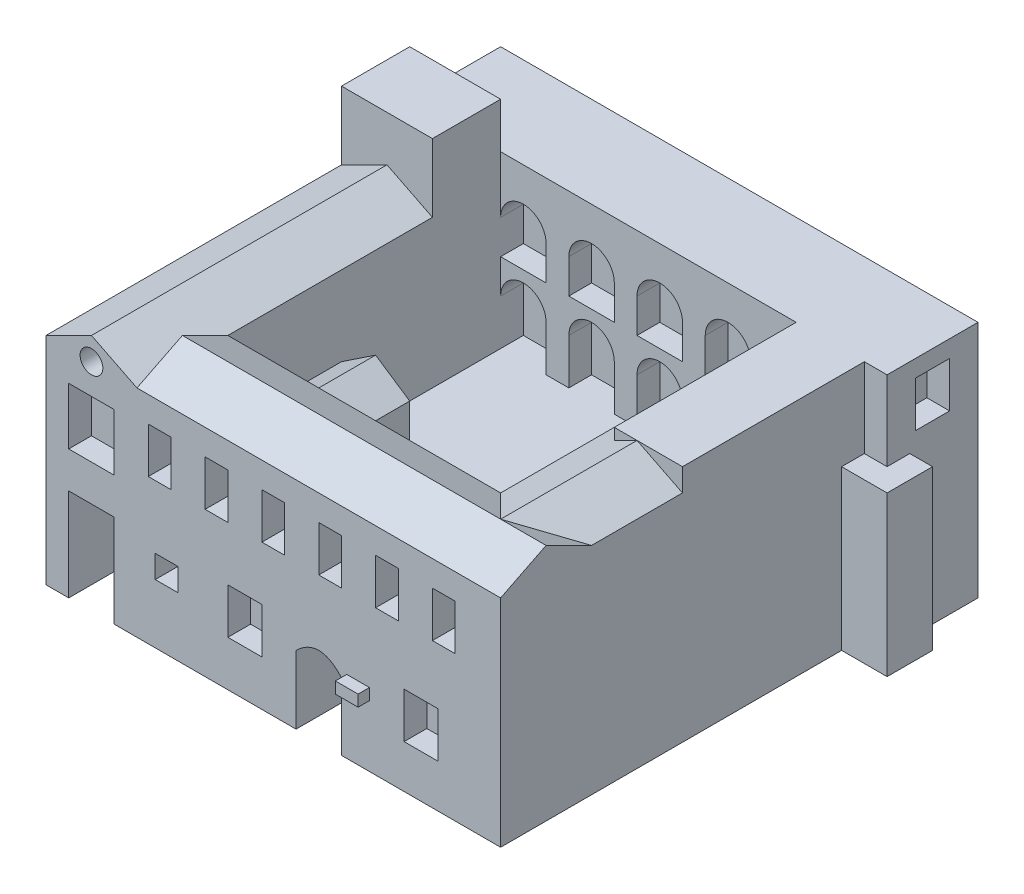
SolidWorks part; units mm, degrees
ref_plane "Alzado" through (0, 0, 0) normal (0, 0, 1) x (1, 0, 0)
ref_plane "Planta" through (0, 0, 0) normal (0, 1, 0) x (1, 0, 0)
ref_plane "Vista lateral" through (0, 0, 0) normal (1, 0, 0) x (0, 0, -1)
sketch "Croquis1" plane through (0, 0, 0) normal (0, 1, 0) x (1, 0, 0)
  line L1 (-10, -10) -> (10, -10)
  line L2 (-10, -10) -> (-10, 10)
  line L3 (-10, 10) -> (10, 10)
  line L4 (10, -10) -> (10, 10)
  line L5 (-10, -10) -> (10, 10) construction
  line L6 (-10, 10) -> (10, -10) construction
  point P0 (0, 0)
  dimension "D1" = 20
  dimension "D2" = 20
extrude "Saliente-Extruir1" add sketch "Croquis1" along normal blind 2
sketch "Croquis2" plane through (0, 2, 0) normal (0, 1, 0) x (1, 0, 0)
  line L0 (-10, 10) -> (-10, -10) construction
  line L1 (-6, -6) -> (6, -6)
  line L2 (-6, -6) -> (-6, 6)
  line L3 (-6, 6) -> (6, 6)
  line L4 (6, -6) -> (6, 6)
  line L5 (-6, -6) -> (6, 6) construction
  line L6 (-6, 6) -> (6, -6) construction
  line L7 (10, 10) -> (-10, 10) construction
  line L12 (10, -10) -> (10, 10)
  line L13 (10, 10) -> (-10, 10)
  line L14 (-10, 10) -> (-10, -10)
  line L15 (-10, -10) -> (10, -10)
  line L16 (10, -10) -> (10, 10)
  line L17 (10, 10) -> (-10, 10)
  line L18 (-10, 10) -> (-10, -10)
  line L19 (-10, -10) -> (10, -10)
  point P0 (0, 0)
  dimension "D1" = 4
  dimension "D2" = 4
  dimension "D3" = 0
extrude "Saliente-Extruir2" add sketch "Croquis2" along normal blind 6.5
sketch "Croquis3" plane through (0, 8.5, 0) normal (0, 1, 0) x (1, 0, 0)
  line L0 (-6, 6) -> (-10, 6) construction
  line L1 (-10, 10) -> (-10, -10) construction
  line L2 (-10, 6) -> (-10, 3) construction
  line L3 (-10, 3) -> (-6, 3) construction
  line L4 (-6, 6) -> (-6, -6) construction
  line L5 (-6, 3) -> (-6, 6) construction
  line L6 (-10, 6) -> (-6, 6)
  line L7 (-6, 6) -> (-6, 3)
  line L8 (-6, 3) -> (-10, 3)
  line L9 (-10, 3) -> (-10, 6)
  dimension "D1" = 3
extrude "Saliente-Extruir3" add sketch "Croquis3" along normal blind 3
sketch "Croquis4" plane through (0, 0, 10) normal (0, 0, 1) x (1, 0, 0)
  line L0 (-10, 8.5) -> (-6, 8.5) construction
  line L1 (-10, 8.5) -> (-8, 9.5)
  line L2 (-8, 9.5) -> (-6, 8.5)
  line L3 (-10, 8.5) -> (-6, 8.5)
  line L4 (-8, 8.5) -> (-8, 10.5037) construction
  dimension "D1" = 1
extrude "Saliente-Extruir4" add sketch "Croquis4" against normal up to surface (13 mm away) up to face at (-8, 10, -3)
sketch "Croquis5" plane through (10, 0, 0) normal (1, 0, 0) x (0, 0, -1)
  line L0 (-10, 8.5) -> (-8, 9.5)
  line L1 (-8, 9.5) -> (-6, 8.5)
  line L2 (-6, 8.5) -> (-10, 8.5)
  line L3 (-8, 8.5) -> (-8, 9.5623) construction
  line L4 (3, 9.5) -> (-10, 9.5) construction
extrude "Saliente-Extruir5" add sketch "Croquis5" against normal blind 16
sketch "Croquis6" plane through (0, 0, -10) normal (0, 0, -1) x (-1, 0, 0)
  line L0 (-10, 8.5) -> (-6, 8.5)
  line L1 (-6, 8.5) -> (-8, 9.5)
  line L2 (6, 9.5) -> (-10, 9.5) construction
  line L3 (-8, 9.5) -> (-10, 8.5)
  line L4 (-8, 8.5) -> (-8, 10.4403) construction
extrude "Saliente-Extruir6" add sketch "Croquis6" against normal up to surface (16 mm away)
sketch "Croquis7" plane through (0, 8.5, 0) normal (0, 1, 0) x (1, 0, 0)
  line L0 (6, 10) -> (10, 10)
  line L1 (10, 10) -> (10, -2)
  line L2 (10, -6) -> (10, 10) construction
  line L3 (10, -2) -> (7, -2)
  line L4 (7, -2) -> (7, 6)
  line L5 (6, 6) -> (6, 10)
  line L6 (6, 10) -> (-10, 10)
  line L7 (-10, 10) -> (-10, 6)
  line L8 (-10, 6) -> (-6, 6)
  line L9 (-6, 6) -> (6, 6)
  line L11 (6, 10) -> (-10, 10)
  line L12 (-10, 10) -> (-10, 6)
  line L13 (-10, 6) -> (-6, 6)
  line L14 (-6, 6) -> (6, 6)
  line L15 (7, 6) -> (6, 6)
  dimension "D2" = 3
  dimension "D3" = 12
  dimension "D1" = 0
extrude "Saliente-Extruir7" add sketch "Croquis7" along normal blind 1
sketch "Croquis8" plane through (0, 0, 0) normal (0, 1, 0) x (1, 0, 0)
  line L0 (10, 10) -> (11, 10)
  line L1 (11, 10) -> (11, 6)
  line L2 (11, 6) -> (10, 6)
  line L3 (10, -2) -> (10, 10) construction
  line L4 (10, 10) -> (10, 6)
  dimension "D1" = 1
  dimension "D2" = 4
extrude "Saliente-Extruir8" add sketch "Croquis8" along normal up to surface (9.5 mm away) up to face at (2, 9.5, -4)
sketch "Croquis9" plane through (0, 0, 0) normal (0, 1, 0) x (1, 0, 0)
  line L0 (10, -2) -> (10, 6) construction
  line L1 (12, 7) -> (10, 7)
  line L2 (12, 7) -> (12, 5)
  line L3 (12, 5) -> (10, 5)
  line L4 (10, 7) -> (10, 5)
  line L5 (12, 7) -> (10, 5) construction
  line L6 (12, 5) -> (10, 7) construction
  point P0 (11, 6)
  dimension "D1" = 2
extrude "Saliente-Extruir9" add sketch "Croquis9" along normal blind 6
sketch "Croquis10" plane through (0, 2, 0) normal (0, 1, 0) x (1, 0, 0)
  line L0 (-6, -6) -> (-6, -5)
  line L1 (-6, 3) -> (-6, -6) construction
  line L2 (-6, -5) -> (6, -5)
  line L3 (6, -6) -> (6, 6) construction
  line L4 (6, -5) -> (6, -6)
  line L5 (-6, -6) -> (6, -6) construction
  line L6 (6, -6) -> (-6, -6)
  dimension "D1" = 1
extrude "Saliente-Extruir10" add sketch "Croquis10" along normal blind 4
sketch "Croquis12" plane through (0, 0, 5) normal (0, 0, -1) x (-1, 0, 0)
  line L2 (3, 5) -> (3, 2)
  line L3 (-6, 2) -> (6, 2) construction
  line L4 (3, 2) -> (6, 2)
  line L5 (6, 2) -> (6, 5)
  line L6 (4.5, 6) -> (4.5, 5) construction
  line L7 (4.5, 5) -> (6, 5) construction
  line L8 (6, 5) -> (3, 5) construction
  line L9 (3, 5) -> (4.5, 6)
  line L10 (4.5, 6) -> (6, 5)
  dimension "D2" = 1
extrude "Saliente-Extruir11" add sketch "Croquis12" along normal blind 4
sketch "Croquis13" plane through (0, 0, 10) normal (0, 0, 1) x (1, 0, 0)
  line L0 (-10, 0) -> (-6, 0) construction
  line L1 (10, 0) -> (10, 8.5) construction
  line L2 (-6, 8.5) -> (10, 8.5) construction
  line L3 (-6, 8.5) -> (10, 8.5) construction
  line L4 (-10, 8.5) -> (-10, 0) construction
  line L5 (-10, 8.5) -> (-6, 8.5) construction
  line L6 (-6, 2.125) -> (1, 2) construction
  line L7 (-9, 0) -> (-7, 0)
  line L9 (-9, 0) -> (-9, 3.0778)
  line L10 (-9, 3.0778) -> (-7, 3.0778)
  line L11 (-7, 0) -> (-7, 3.0778)
  line L12 (-8, 0) -> (-7, 3.0778) construction
  line L13 (-9, 3.0778) -> (-8, 0) construction
  line L14 (-6, 4.25) -> (-10, 4.25) construction
  line L15 (-10, 4.25) -> (-10, 8.5) construction
  line L16 (-6, 4.25) -> (-6, 0) construction
  line L17 (-9, 4.6763) -> (-7, 4.6763)
  line L18 (-9, 4.6763) -> (-9, 7.1763)
  line L19 (-9, 7.1763) -> (-7, 7.1763)
  line L20 (-7, 4.6763) -> (-7, 7.1763)
  line L21 (-9, 4.6763) -> (-7, 7.1763) construction
  line L22 (-9, 7.1763) -> (-7, 4.6763) construction
  line L23 (-6, 0) -> (10, 0) construction
  line L24 (1, 0) -> (1, 2)
  line L26 (3, 1.9643) -> (3, 0)
  line L27 (2, 2) -> (2, 2.5) construction
  line L28 (2.2667, 2.5) -> (1.7333, 2.5) construction
  line L29 (-6, 4.25) -> (-6, 8.5) construction
  line L30 (-6, 6.375) -> (10, 6.375) construction
  line L31 (1, 0) -> (3, 0)
  line L32 (-5.5, 7.375) -> (-4.5, 7.375)
  line L33 (-5.5, 7.375) -> (-5.5, 5.375)
  line L34 (-5.5, 5.375) -> (-4.5, 5.375)
  line L35 (-4.5, 7.375) -> (-4.5, 5.375)
  line L36 (-5.5, 7.375) -> (-4.5, 5.375) construction
  line L37 (-5.5, 5.375) -> (-4.5, 7.375) construction
  line L38 (-3, 5.375) -> (-2, 5.375)
  line L39 (-3, 5.375) -> (-3, 7.375)
  line L40 (-3, 7.375) -> (-2, 7.375)
  line L41 (-2, 5.375) -> (-2, 7.375)
  line L42 (-3, 5.375) -> (-2, 7.375) construction
  line L43 (-3, 7.375) -> (-2, 5.375) construction
  line L44 (-0.5, 5.375) -> (0.5, 5.375)
  line L45 (-0.5, 5.375) -> (-0.5, 7.375)
  line L46 (-0.5, 7.375) -> (0.5, 7.375)
  line L47 (0.5, 5.375) -> (0.5, 7.375)
  line L48 (-0.5, 5.375) -> (0.5, 7.375) construction
  line L49 (-0.5, 7.375) -> (0.5, 5.375) construction
  line L50 (2, 5.375) -> (3, 5.375)
  line L51 (2, 5.375) -> (2, 7.375)
  line L52 (2, 7.375) -> (3, 7.375)
  line L53 (3, 5.375) -> (3, 7.375)
  line L54 (2, 5.375) -> (3, 7.375) construction
  line L55 (2, 7.375) -> (3, 5.375) construction
  line L56 (4.5, 5.375) -> (5.5, 5.375)
  line L57 (4.5, 5.375) -> (4.5, 7.375)
  line L58 (4.5, 7.375) -> (5.5, 7.375)
  line L59 (5.5, 5.375) -> (5.5, 7.375)
  line L60 (4.5, 5.375) -> (5.5, 7.375) construction
  line L61 (4.5, 7.375) -> (5.5, 5.375) construction
  line L62 (7, 5.375) -> (8, 5.375)
  line L63 (7, 5.375) -> (7, 7.375)
  line L64 (7, 7.375) -> (8, 7.375)
  line L65 (8, 5.375) -> (8, 7.375)
  line L66 (7, 5.375) -> (8, 7.375) construction
  line L67 (7, 7.375) -> (8, 5.375) construction
  line L68 (-5.1955, 1.6017) -> (-4.1955, 1.6017)
  line L69 (-5.1955, 1.6017) -> (-5.1955, 2.6017)
  line L70 (-5.1955, 2.6017) -> (-4.1955, 2.6017)
  line L71 (-4.1955, 1.6017) -> (-4.1955, 2.6017)
  line L72 (-5.1955, 1.6017) -> (-4.1955, 2.6017) construction
  line L73 (-5.1955, 2.6017) -> (-4.1955, 1.6017) construction
  line L74 (-2, 3) -> (-0.5, 3)
  line L75 (-2, 3) -> (-2, 1)
  line L76 (-2, 1) -> (-0.5, 1)
  line L77 (-0.5, 3) -> (-0.5, 1)
  line L78 (3.2294, 1.7013) -> (4.2294, 1.7013)
  line L79 (3.2294, 1.7013) -> (3.2294, 2.2013)
  line L80 (3.2294, 2.2013) -> (4.2294, 2.2013)
  line L81 (4.2294, 1.7013) -> (4.2294, 2.2013)
  line L82 (3.2294, 1.7013) -> (4.2294, 2.2013) construction
  line L83 (3.2294, 2.2013) -> (4.2294, 1.7013) construction
  line L84 (5.7519, 0.9018) -> (7.2519, 0.9018)
  line L85 (5.7519, 0.9018) -> (5.7519, 2.9018)
  line L86 (5.7519, 2.9018) -> (7.2519, 2.9018)
  line L87 (7.2519, 0.9018) -> (7.2519, 2.9018)
  line L88 (5.7519, 0.9018) -> (7.2519, 2.9018) construction
  line L89 (5.7519, 2.9018) -> (7.2519, 0.9018) construction
  line L94 (7.8365, 1.3875) -> (9.1766, 2.5) construction
  line L95 (7.6766, 2.5) -> (8.9931, 1.3721) construction
  line L96 (3, 1.9643) -> (9.7814, 1.8432) construction
  circle A0 centre (-8, 8.5) radius 0.5
  circle A1 centre (2, 0) radius 1 construction
  spline S0 degree 3 poles (1, 2) (1.6765, 2.6648) (2.3429, 2.6804) (3, 1.9643) knots 0 0 0 0 1 1 1 1
  point P4 (-8, 0)
  point P20 (-8, 5.9263)
  point P42 (-5, 6.375)
  point P47 (0, 6.375)
  point P48 (-4.9288, 6.4436)
  point P50 (-2.5, 6.375)
  point P58 (2.5, 6.375)
  point P63 (5, 6.375)
  point P68 (7.5, 6.375)
  point P77 (3.7294, 1.9513)
  point P78 (-4.6955, 2.1017)
  point P87 (8.4148, 1.8676)
  point P88 (6.5019, 1.9018)
  dimension "D2" = 1
  dimension "D5" = 2
  dimension "D7" = 1
  dimension "D1" = 1
  dimension "D3" = 2.5
  dimension "D4" = 2
  dimension "D6" = 0.5
  dimension "D8" = 2
  dimension "D9" = 0.5
  dimension "D10" = 1.5
  dimension "D11" = 1
  dimension "D12" = 2
  dimension "D13" = 1
  dimension "D14" = 2
  dimension "D15" = 1.5
  dimension "D16" = 1
  dimension "D17" = 2
  dimension "D18" = 1.5
  dimension "D19" = 1
  dimension "D20" = 2
  dimension "D21" = 1.5
  dimension "D22" = 1
  dimension "D23" = 2
  dimension "D24" = 1.5
  dimension "D25" = 1
  dimension "D26" = 1
  dimension "D27" = 1.5
  dimension "D28" = 2
  dimension "D29" = 6
  dimension "D30" = 4
  dimension "D31" = 1.5
  dimension "1" = 1
  dimension "D32" = 0.5
  dimension "D33" = 2
extrude "Cortar-Extruir1" cut sketch "Croquis13" against normal blind 1
sketch "Croquis14" plane through (0, 0, 9) normal (0, 0, 1) x (1, 0, 0)
  line L4 (-7, 0) -> (-7, 3.0778)
  line L5 (-7, 3.0778) -> (-9, 3.0778)
  line L6 (-9, 3.0778) -> (-9, 0)
  line L7 (-9, 0) -> (-7, 0)
  line L8 (-7, 0) -> (-7, 3.0778)
  line L9 (-7, 3.0778) -> (-9, 3.0778)
  line L10 (-9, 3.0778) -> (-9, 0)
  line L11 (-9, 0) -> (-7, 0)
  dimension "D1" = 0
extrude "Cortar-Extruir2" cut sketch "Croquis14" against normal blind 1 contours L8 L9 L10 L11
sketch "Croquis16" plane through (0, 0, 9) normal (0, 0, 1) x (1, 0, 0)
  line L3 (1, 0) -> (3, 0)
  line L4 (3, 0) -> (3, 1.9643)
  line L5 (1, 2) -> (1, 0)
  line L6 (1, 0) -> (3, 0)
  line L7 (3, 0) -> (3, 1.9643)
  line L8 (1, 2) -> (1, 0)
  spline S1 degree 3 poles (42.0332, -1997.5356) (0.6325, 2582.6492) (-3.6265, -2850.2781) (-179.956, 1991.1915) knots -22.053656 -22.053656 -22.053656 -22.053656 40.605345 40.605345 40.605345 40.605345 only from (3, 1.9643) to (1, 2)
  spline S2 degree 3 poles (3, 1.9643) (2.3429, 2.6804) (1.6765, 2.6648) (1, 2) knots 0 0 0 0 1 1 1 1
  dimension "D1" = 0
extrude "Cortar-Extruir3" cut sketch "Croquis16" against normal blind 1
sketch "Croquis17" plane through (0, 0, 9) normal (0, 0, 1) x (1, 0, 0)
  line L4 (4.2294, 1.7013) -> (4.2294, 2.2013)
  line L5 (4.2294, 2.2013) -> (3.2294, 2.2013)
  line L6 (3.2294, 2.2013) -> (3.2294, 1.7013)
  line L7 (3.2294, 1.7013) -> (4.2294, 1.7013)
  line L8 (4.2294, 1.7013) -> (4.2294, 2.2013)
  line L9 (4.2294, 2.2013) -> (3.2294, 2.2013)
  line L10 (3.2294, 2.2013) -> (3.2294, 1.7013)
  line L11 (3.2294, 1.7013) -> (4.2294, 1.7013)
  dimension "D1" = 0
extrude "Saliente-Extruir13" add sketch "Croquis17" along normal blind 1.5
sketch "Croquis18" plane through (11, 0, 0) normal (1, 0, 0) x (0, 0, -1)
  line L0 (6, 9.5) -> (10, 6) construction
  line L1 (10, 9.5) -> (10, 0) construction
  line L2 (10, 6) -> (10, 9.5) construction
  line L3 (10, 9.5) -> (6, 6) construction
  line L4 (5, 6) -> (7, 6) construction
  line L6 (7.25, 6.75) -> (8.75, 6.75)
  line L7 (7.25, 6.75) -> (7.25, 8.75)
  line L8 (7.25, 8.75) -> (8.75, 8.75)
  line L9 (8.75, 6.75) -> (8.75, 8.75)
  line L10 (7.25, 6.75) -> (8.75, 8.75) construction
  line L11 (7.25, 8.75) -> (8.75, 6.75) construction
  point P5 (8, 7.75)
  dimension "D1" = 1.5
  dimension "D2" = 2
extrude "Cortar-Extruir4" cut sketch "Croquis18" against normal blind 1
sketch "Croquis20" plane through (0, 0, -6) normal (0, 0, 1) x (1, 0, 0)
  line L1 (-6, 2) -> (-6, 5) construction
  line L3 (-6, 9.5) -> (-6, 2) construction
  line L4 (-6, 2) -> (-4, 2) construction
  line L5 (6, 8.5) -> (6, 2) construction
  line L6 (6, 2) -> (6, 5.5) construction
  line L7 (-6, 5) -> (6, 5) construction
  line L8 (6, 2) -> (-6, 2) construction
  line L9 (-4, 2) -> (-3, 2) construction
  line L10 (-3, 2) -> (-1, 2) construction
  line L11 (-1, 2) -> (0, 2) construction
  line L12 (0, 2) -> (2, 2) construction
  line L13 (2, 2) -> (1.6296, 2) construction
  line L14 (1.6296, 2) -> (1.8108, 2) construction
  line L15 (1.8108, 2) -> (3, 2) construction
  line L16 (3, 2) -> (2.4714, 2) construction
  line L17 (2.4714, 2) -> (5, 2) construction
  line L18 (5, 2) -> (6, 2) construction
  line L19 (6, 2) -> (4.9426, 2) construction
  line L20 (4.9426, 2) -> (5.5889, 2) construction
  line L21 (5.5889, 2) -> (6, 2) construction
  line L22 (-6, 5) -> (-6, 5.5) construction
  line L23 (-6, 5.5) -> (6, 5.5) construction
  line L24 (-6, 5.5) -> (-6, 8.5) construction
  line L25 (-5, 2) -> (-5, 8) construction
  line L26 (-2, 2) -> (-2, 8) construction
  line L27 (1, 2) -> (1, 8) construction
  line L28 (3, 2) -> (5, 2) construction
  line L29 (5, 2) -> (4, 2) construction
  line L30 (4, 2) -> (4, 3) construction
  line L31 (-5, 8) -> (-5, 7) construction
  line L32 (-5, 7) -> (-4, 7) construction
  line L33 (-5, 5) -> (-5, 4) construction
  line L34 (-5, 4) -> (-2, 4) construction
  line L35 (1, 7) -> (2, 7) construction
  line L36 (-2, 7) -> (-1, 7) construction
  line L37 (1, 4) -> (4, 4) construction
  line L38 (-2, 4) -> (1, 4) construction
  line L39 (-6, 2) -> (-4, 2)
  line L40 (-4, 2) -> (-4, 4)
  line L41 (-6, 2) -> (-6, 4)
  line L42 (-3, 4) -> (-3, 2)
  line L43 (-3, 2) -> (-1, 2)
  line L44 (-1, 2) -> (-1, 4)
  line L45 (0, 4) -> (0, 2)
  line L46 (0, 2) -> (2, 2)
  line L47 (2, 2) -> (2, 4)
  line L48 (3, 4) -> (3, 2)
  line L49 (3, 2) -> (5, 2)
  line L50 (5, 2) -> (5, 4)
  line L51 (5, 7) -> (5, 5.5)
  line L52 (5, 5.5) -> (3, 5.5)
  line L53 (3, 5.5) -> (3, 7)
  line L54 (4, 4) -> (4, 8) construction
  line L55 (2, 7) -> (2, 5.5)
  line L56 (2, 5.5) -> (0, 5.5)
  line L57 (0, 5.5) -> (0, 7)
  line L58 (3, 7) -> (4, 7) construction
  line L59 (-1, 7) -> (-1, 5.5)
  line L60 (-1, 5.5) -> (-3, 5.5)
  line L61 (-3, 5.5) -> (-3, 7)
  line L62 (0, 7) -> (1, 7) construction
  line L63 (-4, 7) -> (-4, 5.5)
  line L64 (-4, 5.5) -> (-6, 5.5)
  line L65 (-6, 5.5) -> (-6, 7)
  line L66 (-3, 7) -> (-2, 7) construction
  arc A0 (-4, 7) -> (-6, 7) centre (-5, 7) ccw
  arc A1 (-1, 7) -> (-3, 7) centre (-2, 7) ccw
  arc A2 (2, 7) -> (0, 7) centre (1, 7) ccw
  arc A3 (5, 7) -> (3, 7) centre (4, 7) ccw
  arc A4 (5, 4) -> (3, 4) centre (4, 4) ccw
  arc A5 (2, 4) -> (0, 4) centre (1, 4) ccw
  arc A6 (-1, 4) -> (-3, 4) centre (-2, 4) ccw
  arc A7 (-4, 4) -> (-6, 4) centre (-5, 4) ccw
  dimension "D1" = 2
  dimension "D2" = 1
  dimension "D3" = 2
  dimension "D4" = 1
  dimension "D5" = 2
  dimension "D6" = 1
  dimension "D7" = 2
  dimension "D8" = 1
  dimension "D9" = 3
  dimension "D12" = 1
extrude "Cortar-Extruir5" cut sketch "Croquis20" against normal blind 1
sketch "Croquis22" plane through (6, 0, 0) normal (-1, 0, 0) x (0, 0, 1)
  line L0 (-6, 2) -> (-6, 5.1096) construction
  line L1 (-6, 2) -> (-4, 2) construction
  line L2 (-4, 2) -> (-3, 2) construction
  line L3 (-3, 2) -> (-1, 2) construction
  line L4 (-1, 2) -> (0, 2) construction
  line L5 (0, 2) -> (2, 2) construction
  line L6 (2, 2) -> (1.6296, 2) construction
  line L7 (1.6296, 2) -> (1.8108, 2) construction
  line L8 (1.8108, 2) -> (3, 2) construction
  line L9 (3, 2) -> (2.4714, 2) construction
  line L10 (2.4714, 2) -> (5, 2) construction
  line L11 (-6, 5.1096) -> (-6, 5.6096) construction
  line L12 (-6, 5.6096) -> (-6, 8.1096) construction
  line L13 (-5, 2) -> (-5, 8.1096) construction
  line L14 (-2, 2) -> (-2, 8.1704) construction
  line L15 (1, 2) -> (1, 8.1096) construction
  line L16 (3, 2) -> (5, 2) construction
  line L17 (5, 2) -> (4, 2) construction
  line L18 (4, 2) -> (4, 3.1096) construction
  line L19 (-5, 8.1096) -> (-5, 7.1096) construction
  line L20 (-5, 7.1096) -> (-4, 7.1096) construction
  line L21 (-5, 5.0548) -> (-5, 4.0548) construction
  line L22 (-5, 4.0548) -> (-2, 4.0548) construction
  line L23 (1, 7.1096) -> (2, 7.1096) construction
  line L24 (-2, 7.1096) -> (-0.9393, 7.1096) construction
  line L25 (1, 4.0548) -> (4, 4.0548) construction
  line L26 (-2, 4.0548) -> (1, 4.0548) construction
  line L27 (-6, 2) -> (-4, 2)
  line L28 (-4, 2) -> (-4, 4.0548)
  line L29 (-6, 2) -> (-6, 4.0548)
  line L30 (-3, 4.0548) -> (-3, 2)
  line L31 (-3, 2) -> (-1, 2)
  line L32 (-1, 2) -> (-1, 4.0548)
  line L33 (0, 4.0548) -> (0, 2)
  line L34 (0, 2) -> (2, 2)
  line L35 (2, 2) -> (2, 4.0548)
  line L36 (2.9985, 4.0548) -> (3, 2)
  line L37 (3, 2) -> (5, 2)
  line L38 (5, 2) -> (5, 4.1096)
  line L39 (5, 7.1096) -> (5, 5.6096)
  line L40 (5, 5.6096) -> (3, 5.6096)
  line L41 (3, 5.6096) -> (3, 7.1096)
  line L42 (4, 4.0548) -> (4, 8.1096) construction
  line L43 (2, 7.1096) -> (2, 5.6096)
  line L44 (2, 5.6096) -> (0, 5.6096)
  line L45 (0, 5.6096) -> (0, 7.1096)
  line L46 (3, 7.1096) -> (4, 7.1096) construction
  line L47 (-0.9393, 7.1096) -> (-0.9393, 5.6096)
  line L48 (-0.9393, 5.6096) -> (-3.0607, 5.6096)
  line L49 (-3.0607, 5.6096) -> (-3.0607, 7.1096)
  line L50 (0, 7.1096) -> (1, 7.1096) construction
  line L51 (-4, 7.1096) -> (-4, 5.6096)
  line L52 (-4, 5.6096) -> (-6, 5.6096)
  line L53 (-6, 5.6096) -> (-6, 7.1096)
  line L54 (-3.0607, 7.1096) -> (-2, 7.1096) construction
  arc A0 (-4, 7.1096) -> (-6, 7.1096) centre (-5, 7.1096) ccw
  arc A1 (-0.9393, 7.1096) -> (-3.0607, 7.1096) centre (-2, 7.1096) ccw
  arc A2 (2, 7.1096) -> (0, 7.1096) centre (1, 7.1096) ccw
  arc A3 (5, 7.1096) -> (3, 7.1096) centre (4, 7.1096) ccw
  arc A4 (5, 4.1096) -> (2.9985, 4.0548) centre (4, 4.0548) ccw
  arc A5 (2, 4.0548) -> (0, 4.0548) centre (1, 4.0548) ccw
  arc A6 (-1, 4.0548) -> (-3, 4.0548) centre (-2, 4.0548) ccw
  arc A7 (-4, 4.0548) -> (-6, 4.0548) centre (-5, 4.0548) ccw
  dimension "D1" = 2
  dimension "D2" = 1
  dimension "D3" = 2
  dimension "D4" = 1
  dimension "D5" = 2
  dimension "D6" = 1
  dimension "D7" = 1
  dimension "D8" = 1
extrude "Cortar-Extruir6" cut sketch "Croquis22" against normal blind 1
sketch "Croquis26" plane through (0, 0, 5) normal (0, 0, -1) x (-1, 0, 0)
  line L0 (-5, 2) -> (-5, 5.1096) construction
  line L1 (-5, 2) -> (-3, 2) construction
  line L2 (-3, 2) -> (-2, 2.0007) construction
  line L3 (-2, 2.0007) -> (0, 2.0007) construction
  line L4 (0, 2.0007) -> (1, 2.0007) construction
  line L5 (1, 2.0007) -> (3, 2.0007) construction
  line L6 (3, 2.0007) -> (1.1624, 2.0007) construction
  line L7 (1.1624, 2.0007) -> (1.3435, 2.0007) construction
  line L11 (2.0068, 2.1174) -> (4.0068, 2.1174) construction
  line L12 (4.0068, 2.1174) -> (3.0068, 2.1174) construction
  line L13 (3.0068, 2.1174) -> (3.0068, 4.4158) construction
  line L14 (-4, 5.1722) -> (-4, 4.1722) construction
  line L15 (-4, 4.1722) -> (-1, 4.1722) construction
  line L16 (2, 4.1722) -> (3.0068, 4.1722) construction
  line L17 (-1, 4.1722) -> (2, 4.1722) construction
  line L18 (-5, 2) -> (-3, 2)
  line L19 (-3, 2) -> (-3, 4.1722)
  line L20 (-5, 2) -> (-5, 4.1722)
  line L21 (-2, 4.1722) -> (-2, 2.0007)
  line L22 (-2, 2.0007) -> (0, 2.0007)
  line L23 (0, 2.0007) -> (0, 4.1722)
  line L24 (1, 4.1722) -> (1, 2.0007)
  line L25 (1, 2.0007) -> (3, 2.0007)
  line L26 (3, 2.0007) -> (3, 4.1722)
  line L30 (-6, 2) -> (-6, 4.0548) construction
  arc A1 (3, 4.1722) -> (1, 4.1722) centre (2, 4.1722) ccw
  arc A2 (0, 4.1722) -> (-2, 4.1722) centre (-1, 4.1722) ccw
  arc A3 (-3, 4.1722) -> (-5, 4.1722) centre (-4, 4.1722) ccw
  dimension "D8" = 1
  dimension "D9" = 1
  dimension "D1" = 2
  dimension "D2" = 1
  dimension "D3" = 2
  dimension "D4" = 1
  dimension "D5" = 2
  dimension "D6" = 1
  dimension "D7" = 1
  dimension "D11" = 2
  dimension "D14" = 1
extrude "Cortar-Extruir7" cut sketch "Croquis26" against normal blind 1
sketch "Croquis27" plane through (0, 0, 1) normal (0, 0, -1) x (-1, 0, 0)
  line L0 (3.5, 2) -> (3.5, 5.1096) construction
  line L1 (3.5, 2) -> (5.5, 2) construction
  line L2 (4.5, 5.1722) -> (4.5, 4.1722) construction
  line L3 (3.5, 2) -> (5.5, 2)
  line L4 (5.5, 2) -> (5.5, 4.1722)
  line L5 (3.5, 2) -> (3.5, 4.1722)
  line L6 (4.5, 6) -> (4.5, 1.2379) construction
  arc A0 (5.5, 4.1722) -> (3.5, 4.1722) centre (4.5, 4.1722) ccw
extrude "Cortar-Extruir8" cut sketch "Croquis27" against normal blind 2
sketch "Croquis28" plane through (0, 0, 0) normal (0, -1, 0) x (1, 0, 0)
  circle A0 centre (0, 0) radius 1.575
  dimension "D1" = 3.15
sketch "Croquis29" plane through (0, 0, 0) normal (0, -1, 0) x (1, 0, 0)
  line L16 (3, 8) -> (1, 8)
  line L17 (1, 8) -> (1, 10)
  line L18 (1, 10) -> (-7, 10)
  line L19 (-7, 10) -> (-7, 8)
  line L20 (-7, 8) -> (-9, 8)
  line L21 (-9, 8) -> (-9, 10)
  line L22 (-9, 10) -> (-10, 10)
  line L23 (-10, 10) -> (-10, -10)
  line L24 (-10, -10) -> (11, -10)
  line L25 (11, -10) -> (11, -7)
  line L26 (11, -7) -> (12, -7)
  line L27 (12, -7) -> (12, -5)
  line L28 (12, -5) -> (10, -5)
  line L29 (10, -5) -> (10, 10)
  line L30 (10, 10) -> (3, 10)
  line L31 (3, 10) -> (3, 8)
  line L32 (3, 8) -> (1, 8)
  line L33 (1, 8) -> (1, 10)
  line L34 (1, 10) -> (-7, 10)
  line L35 (-7, 10) -> (-7, 8)
  line L36 (-7, 8) -> (-9, 8)
  line L37 (-9, 8) -> (-9, 10)
  line L38 (-9, 10) -> (-10, 10)
  line L39 (-10, 10) -> (-10, -10)
  line L40 (-10, -10) -> (11, -10)
  line L41 (11, -10) -> (11, -7)
  line L42 (11, -7) -> (12, -7)
  line L43 (12, -7) -> (12, -5)
  line L44 (12, -5) -> (10, -5)
  line L45 (10, -5) -> (10, 10)
  line L46 (10, 10) -> (3, 10)
  line L47 (3, 10) -> (3, 8)
  dimension "D1" = 0
extrude "Saliente-Extruir14" add sketch "Croquis29" along normal blind 1
extrude "Cortar-Extruir11" cut sketch "Croquis28" along normal blind 4.25 contours A0
sketch "Croquis30" plane through (0, 0, 0) normal (0, -1, 0) x (1, 0, 0)
  circle A1 centre (0, 0) radius 1.575
  circle A2 centre (0, 0) radius 1.575
  dimension "D1" = 0
extrude "Cortar-Extruir12" cut sketch "Croquis30" against normal blind 1.5
